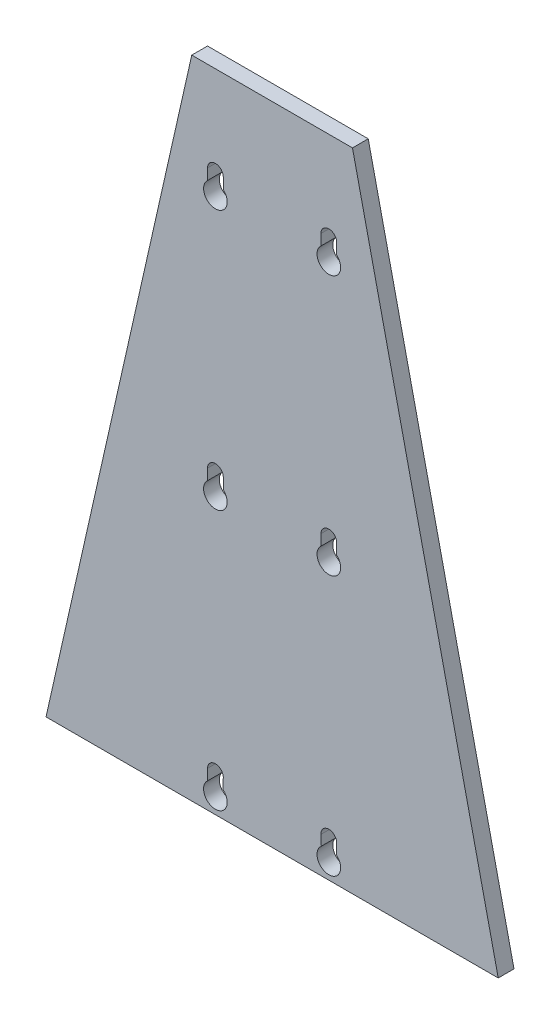
SolidWorks part; units mm, degrees
ref_plane "前视基准面" through (0, 0, 0) normal (0, 0, 1) x (1, 0, 0)
ref_plane "上视基准面" through (0, 0, 0) normal (0, 1, 0) x (1, 0, 0)
ref_plane "右视基准面" through (0, 0, 0) normal (1, 0, 0) x (0, 0, -1)
sketch "草图1" plane through (0, 0, 0) normal (0, 0, 1) x (1, 0, 0)
  line L0 (-41, 0) -> (41, 0)
  line L1 (0, 0) -> (0, -400)
  line L5 (0, -400) -> (0, -410)
  line L6 (-143.5, -410) -> (-51, 0)
  line L7 (-143.5, -410) -> (143.5, -410)
  line L8 (-36, -399.5) -> (-36, -387)
  line L9 (143.5, -410) -> (51, 0)
  line L10 (-41, -387) -> (-41, -393.9098)
  line L12 (-36, -400) -> (-36, -399.5)
  line L13 (-31, -387) -> (-31.1898, -393.7457)
  line L15 (-36, -410) -> (-36, -407)
  line L16 (-36, -407) -> (-36, -399.5)
  line L17 (-36, -387) -> (-36, -222) construction
  line L19 (-36, -222) -> (-36, -234.5)
  line L20 (41, 0) -> (51, 0)
  line L21 (-41, -222) -> (-41, -228.9098)
  line L22 (-31, -222) -> (-31, -228.9098)
  line L23 (41, -387) -> (41, -393.9098)
  line L24 (31, -387) -> (31.1898, -393.7457)
  line L25 (31, -222) -> (31, -228.9098)
  line L26 (41, -222) -> (41, -228.9098)
  line L27 (-36, -222) -> (-36, -57) construction
  line L28 (-41, 0) -> (-51, 0)
  line L29 (-36, -57) -> (-36, -69.5)
  line L30 (-41, -57) -> (-41, -63.9098)
  line L31 (-31, -57) -> (-31, -63.9098)
  line L32 (31, -57) -> (31, -63.9098)
  line L33 (41, -57) -> (41, -63.9098)
  arc A8 (-41, -393.9098) -> (-31.1898, -393.7457) centre (-36, -399.5) ccw
  arc A9 (-31.0079, -387.2811) -> (-41, -387) centre (-36, -387) ccw
  arc A10 (-31, -222) -> (-41, -222) centre (-36, -222) ccw
  arc A11 (-41, -228.9098) -> (-31, -228.9098) centre (-36, -234.5) ccw
  arc A12 (31.0079, -387.2811) -> (41, -387) centre (36, -387) cw
  arc A13 (41, -393.9098) -> (31.1898, -393.7457) centre (36, -399.5) cw
  arc A14 (41, -228.9098) -> (31, -228.9098) centre (36, -234.5) cw
  arc A15 (31, -222) -> (41, -222) centre (36, -222) cw
  arc A16 (-31, -57) -> (-41, -57) centre (-36, -57) ccw
  arc A17 (-41, -63.9098) -> (-31, -63.9098) centre (-36, -69.5) ccw
  arc A18 (41, -63.9098) -> (31, -63.9098) centre (36, -69.5) cw
  arc A19 (31, -57) -> (41, -57) centre (36, -57) cw
  point P4 (0, 0)
  point P10 (0, -400)
  point P15 (0, -400)
  dimension "D1" = 23
  dimension "D4" = 7.5
  dimension "D5" = 5
  dimension "D2" = 102
  dimension "D3" = 287
  dimension "D6" = 12.5
  dimension "D7" = 36
extrude "凸台-拉伸1" add sketch "草图1" along normal blind 10
